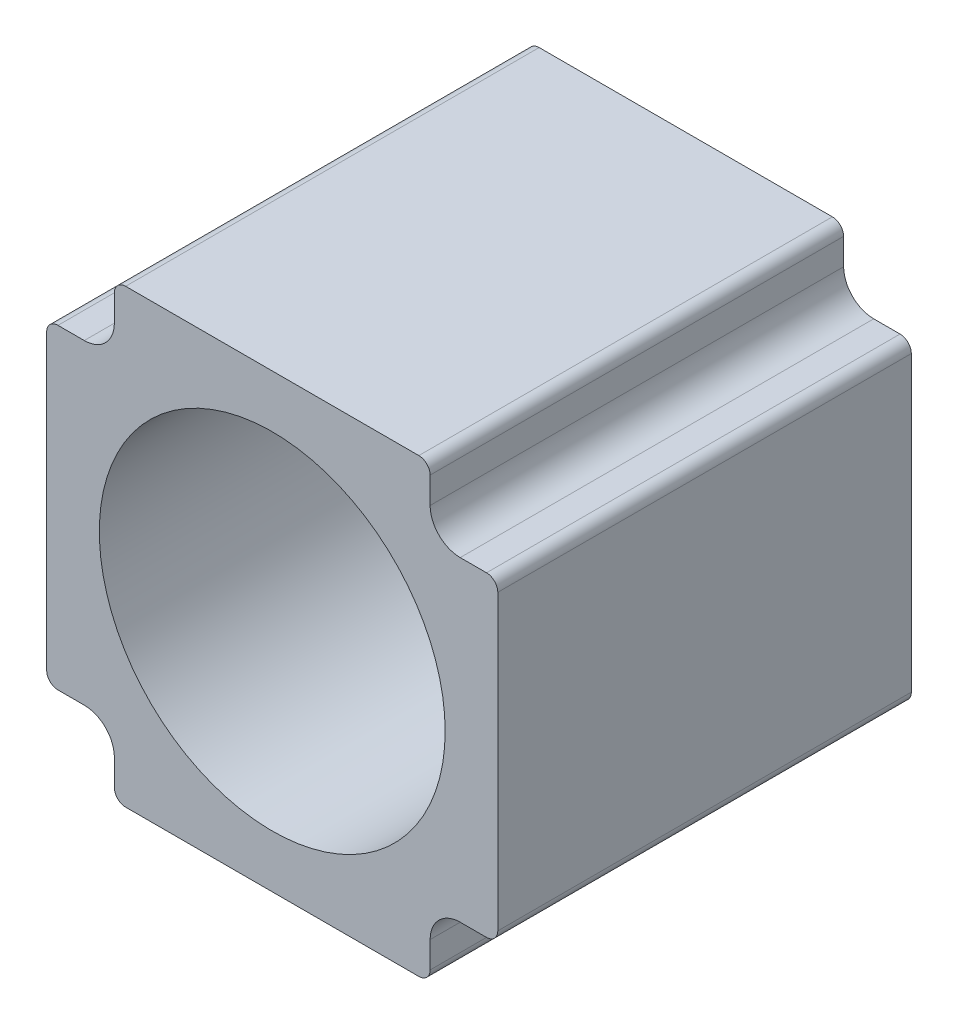
SolidWorks part; units mm, degrees
material "6061 Alloy"
ref_plane "Front Plane" through (0, 0, 0) normal (0, 0, 1) x (1, 0, 0)
ref_plane "Top Plane" through (0, 0, 0) normal (0, 1, 0) x (1, 0, 0)
ref_plane "Right Plane" through (0, 0, 0) normal (1, 0, 0) x (0, 0, -1)
sketch "Sketch1" plane through (0, 0, 0) normal (0, 0, 1) x (1, 0, 0)
  line L0 (30, 0) -> (30, 60) construction
  line L1 (9, 0) -> (51, 0)
  line L2 (0, 9) -> (0, 51)
  line L3 (9, 60) -> (51, 60)
  line L4 (60, 9) -> (60, 51)
  line L6 (51, 60) -> (51, 51)
  line L7 (51, 51) -> (60, 51)
  line L9 (0, 30) -> (60, 30) construction
  line L13 (0, 51) -> (9, 51)
  line L14 (9, 60) -> (9, 51)
  line L15 (0, 9) -> (9, 9)
  line L18 (9, 9) -> (9, 0)
  line L21 (60, 9) -> (51, 9)
  line L22 (51, 0) -> (51, 9)
  dimension "D1" = 60
  dimension "D2" = 60
  dimension "D3" = 9
  dimension "D4" = 9
  dimension "D5" = 9
  dimension "D6" = 9
  dimension "D7" = 9
  dimension "D8" = 9
  dimension "D9" = 9
  dimension "D10" = 9
extrude "Boss-Extrude1" add sketch "Sketch1" along normal blind 55
fillet "Fillet1" radius 4 4 edges at (9, 51, 27.5) (9, 9, 27.5) (51, 9, 27.5) (51, 51, 27.5)
fillet "Fillet2" radius 1.5 8 edges at (60, 51, 27.5) (51, 60, 27.5) (9, 60, 27.5) (0, 51, 27.5) (0, 9, 27.5) (9, 0, 27.5) (51, 0, 27.5) (60, 9, 27.5)
sketch "Sketch2" plane through (0, 0, 55) normal (0, 0, 1) x (1, 0, 0)
  line L0 (30, 69.1598) -> (30, -9.1598) construction
  line L1 (0, 49.5) -> (0, 10.5) construction
  line L2 (49.5, 60) -> (10.5, 60) construction
  circle A0 centre (30, 30) radius 23
  dimension "D2" = 30
  dimension "D1" = 30
extrude "Cut-Extrude1" cut sketch "Sketch2" against normal through all
scale "Scale1" scale about centroid uniform scaling yes scale factor 2.3
